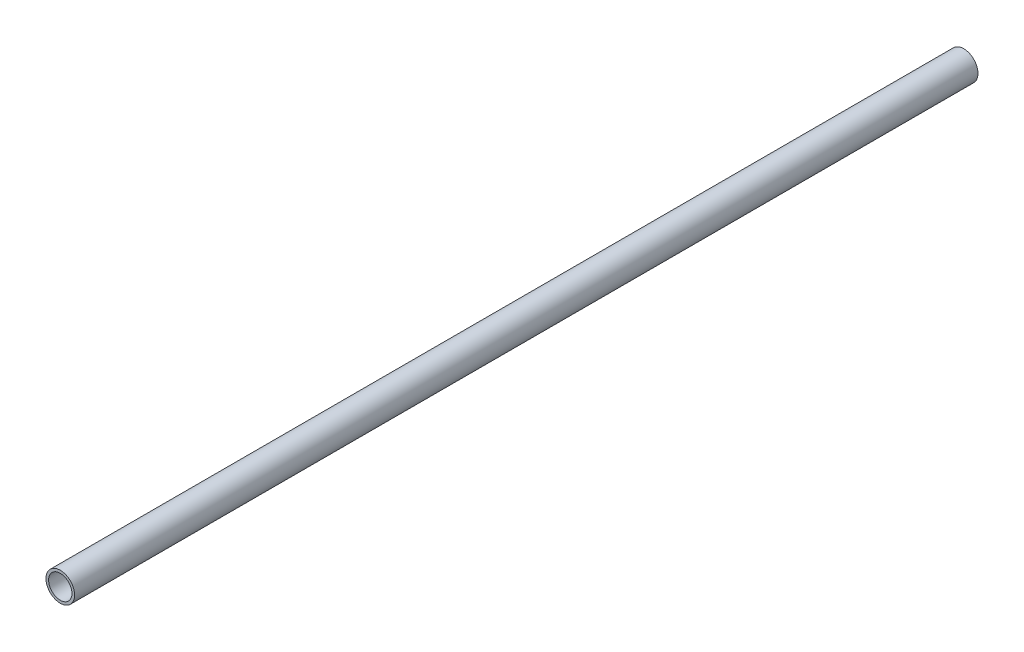
SolidWorks part; units mm, degrees
ref_plane "Front Plane" through (0, 0, 0) normal (0, 0, 1) x (1, 0, 0)
ref_plane "Top Plane" through (0, 0, 0) normal (0, 1, 0) x (1, 0, 0)
ref_plane "Right Plane" through (0, 0, 0) normal (1, 0, 0) x (0, 0, -1)
sketch "Sketch1" plane through (0, 0, 0) normal (0, 0, 1) x (1, 0, 0)
  circle A0 centre (0, 0) radius 14.1
  circle A1 centre (0, 0) radius 11.5
  dimension "D2" = 28.2
  dimension "D1" = 2.6
extrude "Boss-Extrude1" add sketch "Sketch1" along normal mid plane 890
ref_point "Point1"
ref_point "Point2"
